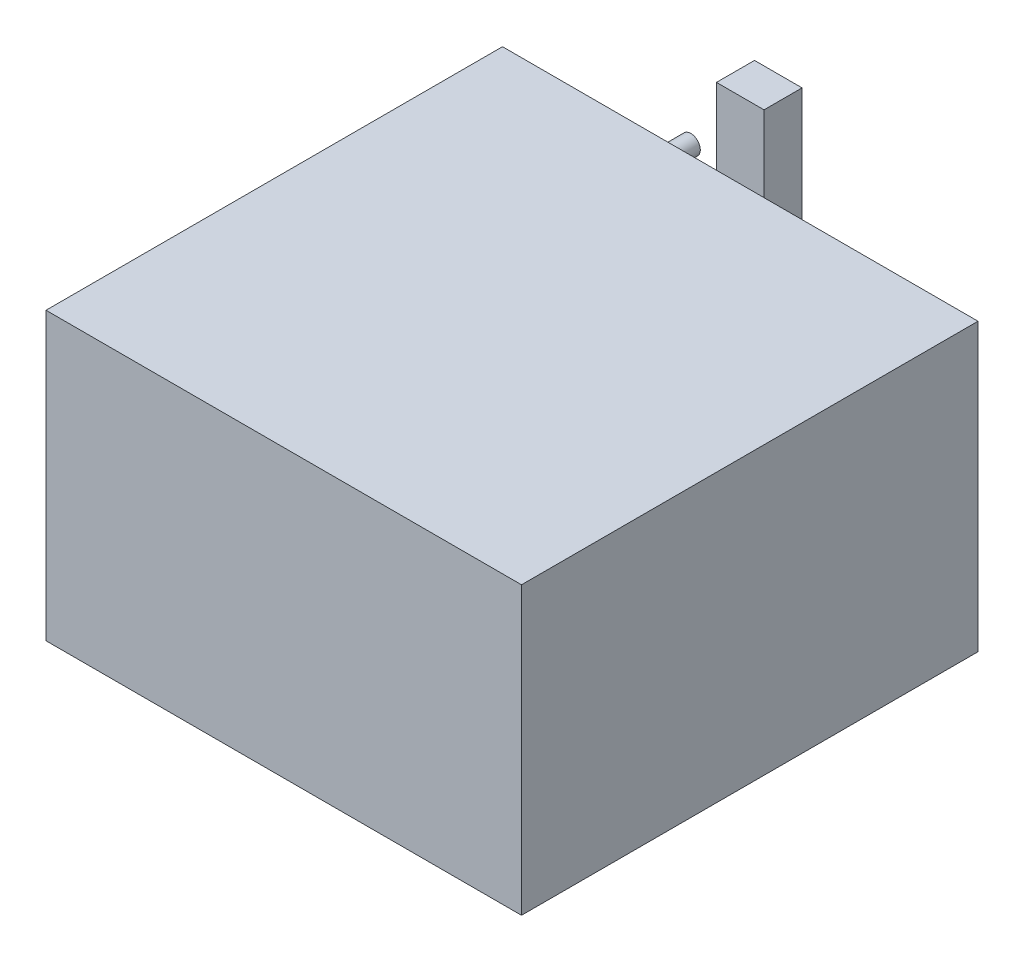
SolidWorks part; units mm, degrees
ref_plane "Спереди" through (0, 0, 0) normal (0, 0, 1) x (1, 0, 0)
ref_plane "Сверху" through (0, 0, 0) normal (0, 1, 0) x (1, 0, 0)
ref_plane "Справа" through (0, 0, 0) normal (1, 0, 0) x (0, 0, -1)
sketch "Эскиз2" plane through (0, 0, 0) normal (0, 0, 1) x (1, 0, 0)
  line L1 (-29.5791, 25.0682) -> (-4.5791, 25.0682)
  line L2 (-29.5791, 25.0682) -> (-29.5791, 10.0182)
  line L3 (-29.5791, 10.0182) -> (-4.5791, 10.0182)
  line L4 (-4.5791, 25.0682) -> (-4.5791, 10.0182)
extrude "Бобышка-Вытянуть2" add sketch "Эскиз2" along normal blind 24
sketch "Эскиз3" plane through (0, 0, 0) normal (0, 0, -1) x (-1, 0, 0)
  line L4 (29.5791, 25.0682) -> (29.5791, 10.0182) construction
  circle A5 centre (24.6791, 20.5682) radius 0.5
  circle A6 centre (24.6791, 14.5682) radius 0.5
  dimension "D1" = 4.9
extrude "Бобышка-Вытянуть3" add sketch "Эскиз3" along normal blind 5
sketch "Эскиз4" plane through (0, 0, 0) normal (0, 0, -1) x (-1, 0, 0)
  line L0 (15.8291, 22.0682) -> (18.3291, 22.0682)
  line L1 (15.8291, 22.0682) -> (15.8291, 29.0682)
  line L2 (15.8291, 29.0682) -> (18.3291, 29.0682)
  line L3 (18.3291, 22.0682) -> (18.3291, 29.0682)
  line L4 (15.8291, 13.0182) -> (18.3291, 13.0182)
  line L5 (15.8291, 13.0182) -> (15.8291, 6.0182)
  line L6 (15.8291, 6.0182) -> (18.3291, 6.0182)
  line L7 (18.3291, 13.0182) -> (18.3291, 6.0182)
  line L8 (29.5791, 10.0182) -> (4.5791, 10.0182) construction
  line L9 (4.5791, 25.0682) -> (29.5791, 25.0682) construction
  line L10 (4.5791, 10.0182) -> (4.5791, 25.0682) construction
  line L11 (16.8692, -0.7228) -> (16.8692, 34.8702) construction
  dimension "D1" = 3
  dimension "D2" = 3
  dimension "D3" = 4
  dimension "D4" = 4
  dimension "D5" = 2.5
  dimension "D6" = 2.5
  dimension "D7" = 11.25
  dimension "D8" = 11.25
extrude "Бобышка-Вытянуть4" add sketch "Эскиз4" along normal blind 2
